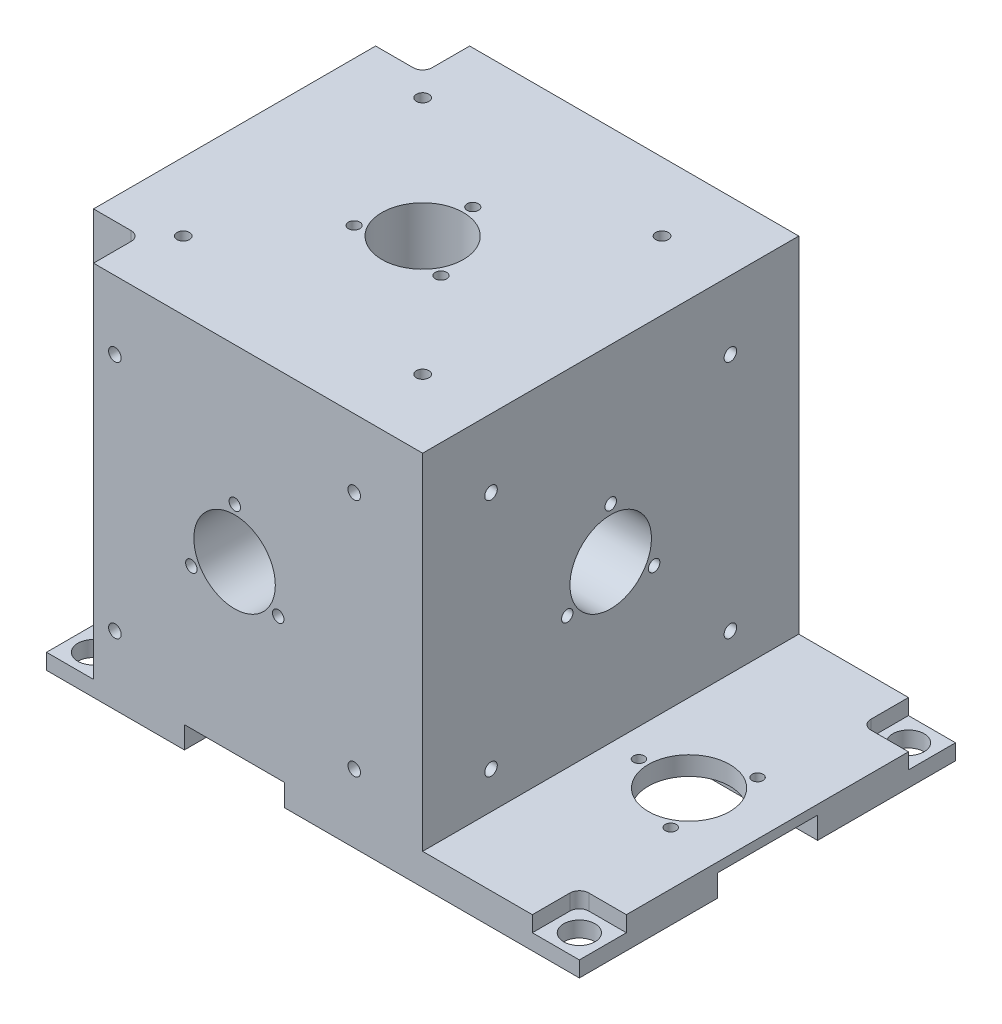
SolidWorks part; units mm, degrees
ref_plane "Front Plane" through (0, 0, 0) normal (0, 0, 1) x (1, 0, 0)
ref_plane "Top Plane" through (0, 0, 0) normal (0, 1, 0) x (1, 0, 0)
ref_plane "Right Plane" through (0, 0, 0) normal (1, 0, 0) x (0, 0, -1)
sketch "Sketch1" plane through (0, 0, 0) normal (0, 1, 0) x (1, 0, 0)
  line L0 (-60, 60) -> (-60, -60)
  line L1 (0, 60) -> (-60, 60)
  line L2 (0, 60) -> (60, 60)
  line L3 (-60, -60) -> (60, -60)
  line L4 (60, 60) -> (60, -60)
extrude "Boss-Extrude1" add sketch "Sketch1" along normal blind 120 contours L1 L0 L3 L4 L2
sketch "Sketch3" plane through (60, 0, 0) normal (1, 0, 0) x (0, 0, -1)
  line L0 (-60, 0) -> (-60, 10)
  line L1 (-60, 120) -> (-60, 0) construction
  line L2 (-60, 10) -> (60, 10)
  line L3 (60, 120) -> (60, 0) construction
  line L4 (60, 10) -> (60, 0)
  line L5 (60, 0) -> (-60, 0)
extrude "Boss-Extrude2" add sketch "Sketch3" along normal blind 50
sketch "Sketch4" plane through (0, 0, 0) normal (0, -1, 0) x (1, 0, 0)
  line L0 (16, 16) -> (110, 16)
  line L1 (16, -16) -> (110, -16)
  line L2 (110, -16) -> (110, 16)
  line L3 (-16, -16) -> (-16, -60)
  line L4 (110, -60) -> (-60, -60) construction
  line L5 (-16, 16) -> (-16, 60)
  line L6 (-60, 60) -> (110, 60) construction
  line L7 (16, -16) -> (16, -60)
  line L8 (16, 16) -> (16, 60)
  line L9 (-16, 16) -> (-60, 16)
  line L10 (-60, -60) -> (-60, 60) construction
  line L11 (-16, -16) -> (-60, -16)
  line L12 (16, -60) -> (-16, -60)
  line L13 (-60, -16) -> (-60, 16)
  line L14 (16, 60) -> (-16, 60)
sketch "Sketch7" plane through (-60, 0, 0) normal (-1, 0, 0) x (0, 0, 1)
  circle A0 centre (0, 60) radius 13
  circle A1 centre (0, 76) radius 1.825
  circle A2 centre (13.8564, 52) radius 1.825
  circle A3 centre (-13.8564, 52) radius 1.825
  circle A7 centre (-38.1838, 98.1838) radius 2
  circle A8 centre (38.1838, 98.1838) radius 2
  circle A9 centre (38.1838, 21.8162) radius 2
  circle A10 centre (-38.1838, 21.8162) radius 2
  point P2 (-38.1838, 98.1838)
  point P10 (0, 60)
  point P14 (0, 60)
  point P18 (0, 60)
  dimension "D1" = 3
sketch "Sketch8" plane through (0, 0, -60) normal (0, 0, -1) x (-1, 0, 0)
  circle A0 centre (0, 60) radius 13
  circle A1 centre (0, 76) radius 1.825
  circle A2 centre (13.8564, 52) radius 1.825
  circle A3 centre (-13.8564, 52) radius 1.825
  circle A7 centre (-38.1838, 98.1838) radius 2
  circle A8 centre (38.1838, 98.1838) radius 2
  circle A9 centre (38.1838, 21.8162) radius 2
  circle A10 centre (-38.1838, 21.8162) radius 2
  point P0 (-38.1838, 98.1838)
  point P13 (0, 60)
  point P17 (0, 60)
  point P18 (0, 60)
sketch "Sketch10" plane through (0, 120, 0) normal (0, 1, 0) x (1, 0, 0)
  circle A0 centre (0, 0) radius 13
  circle A1 centre (0, 16) radius 1.825
  circle A2 centre (13.8564, -8) radius 1.825
  circle A3 centre (-13.8564, -8) radius 1.825
  point P10 (0, 0)
  point P14 (0, 0)
sketch "Sketch11" plane through (0, 0, 60) normal (0, 0, 1) x (1, 0, 0)
  line L0 (0, 0) -> (0, 120)
  line L1 (-60, 120) -> (60, 120) construction
  circle A4 centre (0, 60) radius 13
  circle A5 centre (0, 76) radius 1.825
  circle A6 centre (13.8564, 52) radius 1.825
  circle A7 centre (-13.8564, 52) radius 1.825
  point P10 (0, 60)
  point P14 (0, 60)
sketch "Sketch13" plane through (60, 0, 0) normal (1, 0, 0) x (0, 0, -1)
  circle A0 centre (0, 60) radius 13
  circle A1 centre (0, 76) radius 1.825
  circle A2 centre (13.8564, 52) radius 1.825
  circle A3 centre (-13.8564, 52) radius 1.825
  point P5 (0, 60)
  point P9 (0, 60)
extrude "Cut-Extrude3" cut sketch "Sketch11" against normal blind 120 contours A4
extrude "Cut-Extrude6" cut sketch "Sketch7" against normal blind 5 contours A2 | A1 | A3 | A10 | A7 | A9 | A8
extrude "Cut-Extrude12" cut sketch "Sketch4" against normal blind 4 contours L1 L2 L0 L8 L14 L5 L9 L13 L11 L3 L12 L7
extrude "Cut-Extrude13" cut sketch "Sketch10" against normal blind 116 contours A0
extrude "Cut-Extrude14" cut sketch "Sketch8" against normal blind 5 contours A2 | A1 | A3 | A7 | A10 | A9 | A8
extrude "Cut-Extrude17" cut sketch "Sketch13" against normal blind 120 contours A0
sketch "Sketch17" plane through (0, 10, 0) normal (0, 1, 0) x (1, 0, 0)
  circle A0 centre (85, 0) radius 13
extrude "Cut-Extrude18" cut sketch "Sketch17" against normal blind 6 contours A0
sketch "Sketch18" plane through (0, 10, 0) normal (0, 1, 0) x (1, 0, 0)
  line L0 (110, 0) -> (60, 0)
  line L1 (110, 60) -> (110, -60) construction
  line L2 (60, 60) -> (60, -60) construction
  line L3 (85, 0) -> (69, 0)
  circle A0 centre (93, 13.8564) radius 1.75
  circle A1 centre (69, 0) radius 1.75
  circle A2 centre (93, -13.8564) radius 1.75
  point P16 (85, 0)
  dimension "D1" = 3
extrude "Cut-Extrude19" cut sketch "Sketch18" against normal blind 6 contours A2 | A0 | A1
fillet "Fillet1" radius 3 4 edges at (16, 2, 16) (-16, 2, 16) (-16, 2, -16) (16, 2, -16)
fillet "Fillet2" radius 3 1 edges at (0, 4, 13)
chamfer "Chamfer1" distance 3 angle 45 4 edges at (110, 4, 0) (0, 4, 60) (-60, 4, 0) (0, 4, -60)
sketch "Sketch19" plane through (0, 120, 0) normal (0, 1, 0) x (1, 0, 0)
  line L0 (-60, 60) -> (-45, 60)
  line L3 (-60, 60) -> (-60, -60) construction
  line L4 (-60, 45) -> (-60, 60)
  line L5 (-60, -45) -> (-45, -45)
  line L6 (-45, -45) -> (-45, -60)
  line L7 (-45, -60) -> (-60, -60)
  line L8 (-60, -60) -> (-60, -45)
  line L9 (-60, -60) -> (-55, -60)
  line L10 (-60, -60) -> (60, -60) construction
  line L11 (-45, 60) -> (-45, 45)
  line L12 (-45, 45) -> (-60, 45)
extrude "Cut-Extrude20" cut sketch "Sketch19" against normal blind 115 contours L12 L4 L0 L11 | L5 L6 L7 L8
sketch "Sketch20" plane through (0, 5, 0) normal (0, 1, 0) x (1, 0, 0)
  circle A0 centre (-52.5, 52.5) radius 5
  circle A1 centre (-52.5, -52.5) radius 5
extrude "Cut-Extrude21" cut sketch "Sketch20" against normal blind 5 contours A0 | A1
fillet "Fillet3" radius 3 2 edges at (-45, 62.5, 45) (-45, 62.5, -45)
sketch "Sketch21" plane through (0, 10, 0) normal (0, 1, 0) x (1, 0, 0)
  line L0 (110, -60) -> (95, -60)
  line L1 (110, -60) -> (60, -60) construction
  line L2 (95, -60) -> (95, -45)
  line L3 (95, -45) -> (110, -45)
  line L4 (110, 60) -> (110, -60) construction
  line L5 (110, -45) -> (110, -60)
  line L6 (110, 45) -> (95, 45)
  line L7 (95, 45) -> (95, 60)
  line L8 (95, 60) -> (110, 60)
  line L9 (110, 60) -> (110, 45)
  line L10 (110, 60) -> (95, 60)
  line L11 (110, 60) -> (60, 60) construction
extrude "Cut-Extrude22" cut sketch "Sketch21" against normal blind 5 contours L3 L2 L5 L10 | L7 L6 L10 L11
sketch "Sketch22" plane through (0, 5, 0) normal (0, 1, 0) x (1, 0, 0)
  circle A0 centre (102.5, 52.5) radius 5
  circle A1 centre (102.5, -52.5) radius 5
extrude "Cut-Extrude23" cut sketch "Sketch22" against normal blind 5
fillet "Fillet4" radius 3 2 edges at (95, 7.5, -45) (95, 7.5, 45)
sketch "Sketch23" plane through (0, 0, 60) normal (0, 0, 1) x (1, 0, 0)
  circle A0 centre (0.0779, 75.9221) radius 1.825
  circle A1 centre (13.9343, 51.9221) radius 1.825
  circle A2 centre (-13.7785, 51.9221) radius 1.825
  circle A3 centre (-38.1838, 98.1838) radius 2
  circle A4 centre (38.1838, 98.1838) radius 2
  circle A5 centre (38.1838, 21.8162) radius 2
  circle A6 centre (-38.1838, 21.8162) radius 2
  point P0 (-38.1838, 98.1838)
  point P8 (0, 60)
  point P10 (0.0779, 59.9221)
  point P17 (0, 60)
extrude "Cut-Extrude24" cut sketch "Sketch23" against normal blind 5
sketch "Sketch24" plane through (60, 0, 0) normal (1, 0, 0) x (0, 0, -1)
  circle A9 centre (0, 76) radius 1.825
  circle A10 centre (13.8564, 52) radius 1.825
  circle A11 centre (-13.8564, 52) radius 1.825
  circle A12 centre (-38.1838, 98.1838) radius 2
  circle A13 centre (38.1838, 98.1838) radius 2
  circle A14 centre (38.1838, 21.8162) radius 2
  circle A15 centre (-38.1838, 21.8162) radius 2
  point P2 (-38.1838, 98.1838)
  point P8 (0, 60)
  point P12 (0, 60)
  point P13 (0, 60)
extrude "Cut-Extrude25" cut sketch "Sketch24" against normal blind 5
sketch "Sketch26" plane through (0, 120, 0) normal (0, 1, 0) x (1, 0, 0)
  circle A1 centre (0, 16) radius 1.825
  circle A2 centre (13.8564, -8) radius 1.825
  circle A3 centre (-13.8564, -8) radius 1.825
  circle A4 centre (-38.1838, 38.1838) radius 2
  circle A5 centre (38.1838, 38.1838) radius 2
  circle A6 centre (38.1838, -38.1838) radius 2
  circle A7 centre (-38.1838, -38.1838) radius 2
  point P2 (-38.1838, 38.1838)
  point P8 (0, 0)
  point P12 (0, 0)
  point P13 (0, 0)
extrude "Cut-Extrude26" cut sketch "Sketch26" against normal blind 5
